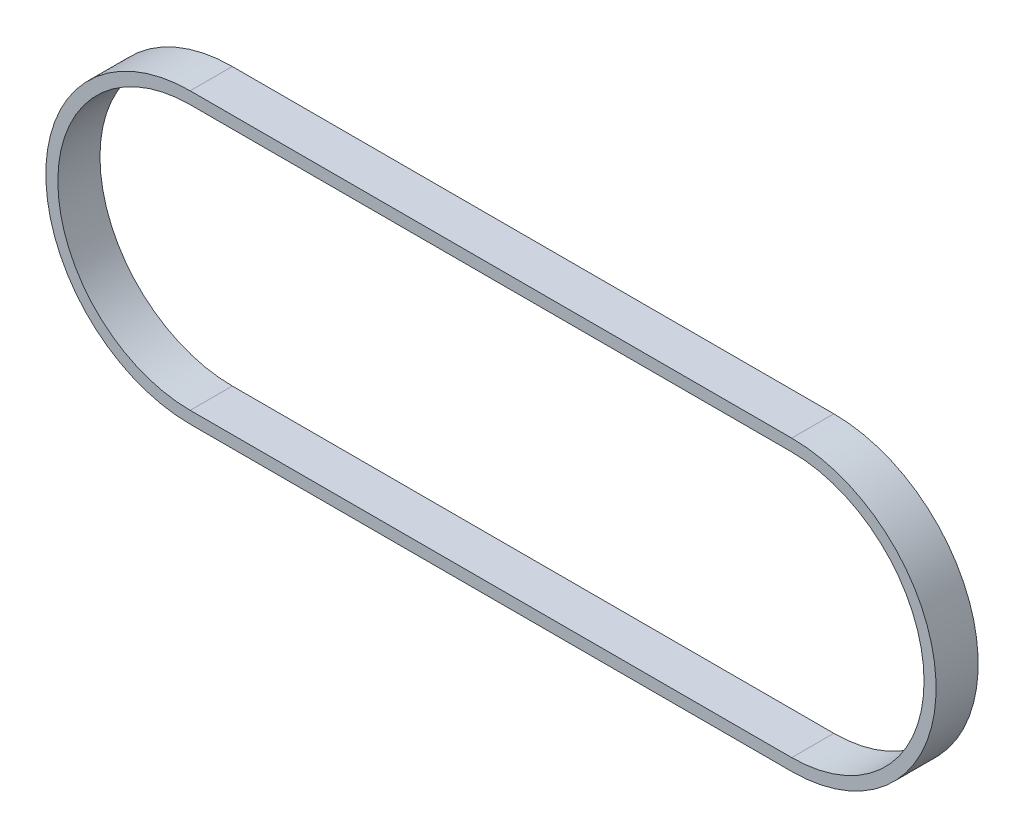
SolidWorks part; units mm, degrees
ref_plane "Front Plane" through (0, 0, 0) normal (0, 0, 1) x (1, 0, 0)
ref_plane "Top Plane" through (0, 0, 0) normal (0, 1, 0) x (1, 0, 0)
ref_plane "Right Plane" through (0, 0, 0) normal (1, 0, 0) x (0, 0, -1)
sketch "Sketch1" plane through (0, 0, 0) normal (0, 0, 1) x (1, 0, 0)
  line L0 (0, 33) -> (150, 33)
  line L1 (0, -33) -> (150, -33)
  line L2 (0, 36) -> (150, 36)
  line L3 (0, -36) -> (150, -36)
  circle A0 centre (0, 0) radius 33
  circle A1 centre (150, 0) radius 33
  circle A2 centre (0, 0) radius 36
  circle A3 centre (150, 0) radius 36
  dimension "D1" = 66
  dimension "D2" = 66
  dimension "D4" = 72
  dimension "D5" = 72
  dimension "D3" = 150
  dimension "D6" = 72
extrude "Boss-Extrude1" add sketch "Sketch1" along normal blind 10.5 contours L0 A2 L1 A0 | A3 L2 A2 L0 | A3 L0 A1 L1 | A3 L1 A2 L3
